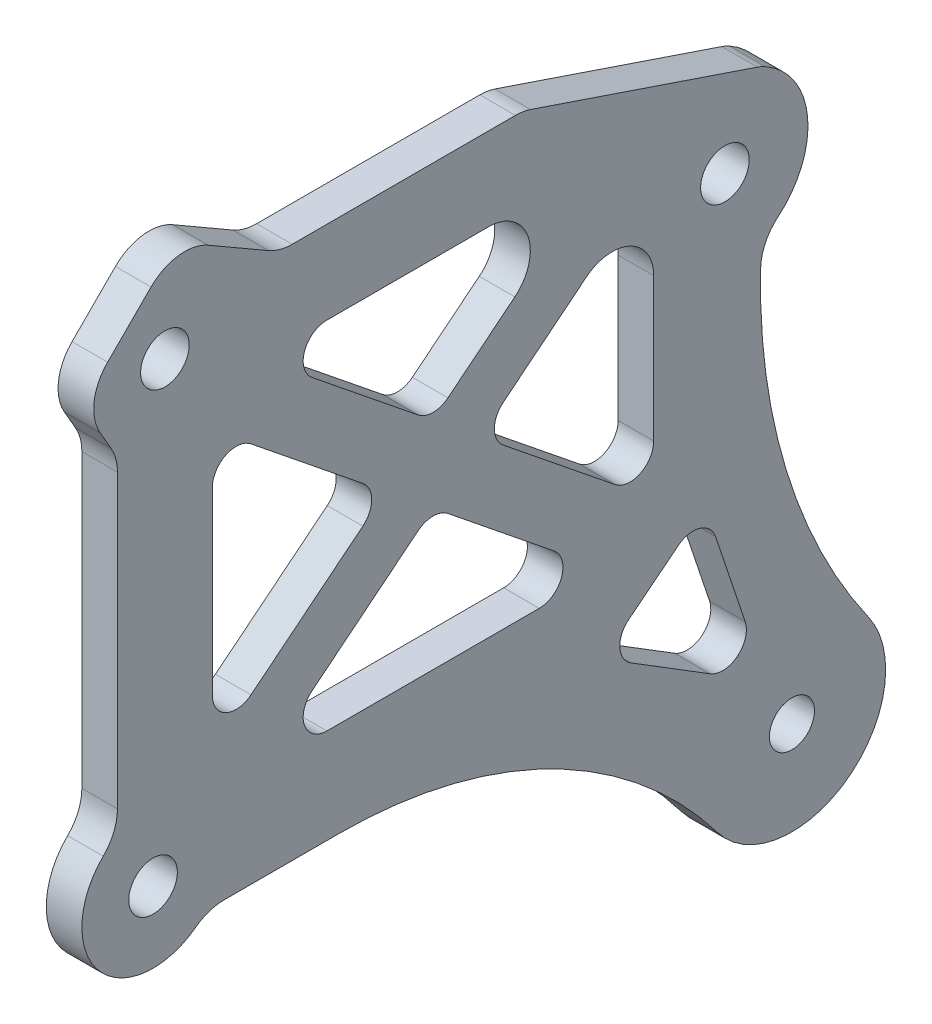
SolidWorks part; units mm, degrees
material "Thornel Mat VMA"
ref_plane "前视基准面" through (0, 0, 0) normal (0, 0, 1) x (1, 0, 0)
ref_plane "上视基准面" through (0, 0, 0) normal (0, 1, 0) x (1, 0, 0)
ref_plane "右视基准面" through (0, 0, 0) normal (1, 0, 0) x (0, 0, -1)
sketch "草图1" plane through (0, 0, 0) normal (1, 0, 0) x (0, 0, -1)
  line L25 (1, 37.9868) -> (63, -4.0132) construction
  line L26 (-3, -4) -> (48.2719, -4) construction
  line L31 (-3, -4) -> (-3, 40.9868) construction
  line L32 (-3, 40.9868) -> (51.2, 40.9868)
  line L34 (1, 37.9868) -> (63, 37.9868) construction
  line L35 (1, 37.9868) -> (1, -4.0132) construction
  line L36 (1, -4.0132) -> (63, -4.0132) construction
  line L37 (63, 37.9868) -> (63, -4.0132) construction
  line L38 (1, 37.9868) -> (53.8469, -15.0717) construction
  line L39 (1, 37.9868) -> (67.6564, 3.8558) construction
  line L41 (48.2719, -9.4744) -> (48.2719, -4) construction
  line L44 (-3, 40.9868) -> (-3, 5.1962)
  line L45 (4.4721, -4) -> (15.6689, -4)
  line L46 (51.2, 34.2246) -> (51.2, 40.9868)
  line L47 (38.2165, 33.9868) -> (23.6, 22.2045)
  line L48 (42.2, 4) -> (5, 4) construction
  line L49 (42.2, 4) -> (42.2, 33.9868) construction
  line L50 (42.2, 33.9868) -> (5, 33.9868) construction
  line L51 (5, 4) -> (5, 33.9868) construction
  line L52 (42.2, 4) -> (5, 33.9868) construction
  line L53 (42.2, 33.9868) -> (5, 4) construction
  line L54 (8.9835, 4) -> (23.6, 15.7823)
  line L55 (8.9835, 33.9868) -> (23.6, 22.2045)
  line L56 (5, 30.7757) -> (19.6165, 18.9934)
  line L57 (8.9835, 33.9868) -> (38.2165, 33.9868)
  line L58 (42.2, 30.7757) -> (42.2, 7.2111)
  line L59 (8.9835, 4) -> (38.2165, 4)
  line L60 (5, 30.7757) -> (5, 7.2111)
  line L61 (19.6165, 18.9934) -> (5, 7.2111)
  line L62 (27.5835, 18.9934) -> (42.2, 7.2111)
  line L63 (27.5835, 18.9934) -> (42.2, 30.7757)
  line L64 (23.6, 15.7823) -> (38.2165, 4)
  circle A0 centre (0, 0) radius 2.05
  circle A1 centre (48.2, 27.9) radius 2.05
  circle A4 centre (1, 37.9868) radius 2.05
  circle A5 centre (63, -4.0132) radius 1.9 construction
  arc A6 (53.8469, -15.0717) -> (67.6564, 3.8558) centre (1, 37.9868) ccw construction
  arc A7 (55.1877, -16.4178) -> (69.3476, 2.9898) centre (1, 37.9868) ccw construction
  arc A8 (52.5061, -13.7255) -> (65.9652, 4.7218) centre (1, 37.9868) ccw construction
  arc A9 (52.5061, -13.7255) -> (55.1877, -16.4178) centre (53.8469, -15.0717) ccw construction
  arc A10 (69.3476, 2.9898) -> (65.9652, 4.7218) centre (67.6564, 3.8558) ccw construction
  arc A11 (53.8469, -15.0717) -> (67.6564, 3.8558) centre (1, 37.9868) ccw construction
  arc A12 (59.4219, -20.669) -> (74.6881, 0.2552) centre (1, 37.9868) ccw construction
  arc A13 (48.2719, -9.4744) -> (60.6246, 7.4564) centre (1, 37.9868) ccw construction
  arc A14 (48.2719, -9.4744) -> (59.4219, -20.669) centre (53.8469, -15.0717) ccw construction
  arc A15 (74.6881, 0.2552) -> (60.6246, 7.4564) centre (67.6564, 3.8558) ccw construction
  circle A19 centre (53.8469, -15.0717) radius 1.9
  arc A20 (-3, 5.1962) -> (4.4721, -4) centre (0, 0) ccw
  arc A21 (47.5503, -19.8427) -> (15.6689, -4) centre (15.6689, -44) ccw
  arc A22 (47.5503, -19.8427) -> (59.4219, -20.669) centre (53.8469, -15.0717) ccw
  arc A23 (51.3147, 21.6311) -> (60.3079, -10.5257) centre (101.2, 18.2464) ccw
  arc A24 (59.4219, -20.669) -> (60.3079, -10.5257) centre (53.8469, -15.0717) ccw
  arc A25 (51.3147, 21.6311) -> (51.2, 34.2246) centre (48.2, 27.9) ccw
  point P8 (23.6, 18.9934)
  point P17 (61.4965, -6.1513)
  point P26 (61.4965, -6.1513)
  dimension "D3" = 4.1
  dimension "D4" = 3
  dimension "D9" = 4
  dimension "D6" = 3
  dimension "D7" = 3
  dimension "D8" = 4.1
  dimension "D10" = 37.9868
  dimension "D13" = 3.8
  dimension "D14" = 11
  dimension "D16" = 6
  dimension "D17" = 12
  dimension "D18" = 40
  dimension "D20" = 14
  dimension "D1" = 27.9
  dimension "D2" = 48.2
  dimension "D5" = 4
  dimension "D11" = 62
  dimension "D12" = 42
  dimension "D15" = 7
  dimension "D19" = 50
  dimension "D21" = 8
  dimension "D22" = 7
  dimension "D23" = 6
  dimension "D24" = 8
  dimension "D25" = 5
  dimension "D26" = 5
extrude "凸台-拉伸1" add sketch "草图1" along normal blind 3
sketch "草图2" plane through (3, 0, 0) normal (1, 0, 0) x (0, 0, -1)
  line L1 (2, 45.9868) -> (-3, 40.9868)
  line L2 (-3.867, 15.4678) -> (-3, -4) construction
  line L3 (-3, 40.9868) -> (-6, 37.9868)
  line L4 (-3, 40.9868) -> (-3, -4) construction
  line L7 (-3, 40.9868) -> (-3, -1.0781) construction
  line L8 (4.4721, -4) -> (15.6689, -4) construction
  line L9 (-6, 37.9868) -> (-3, 32.7907)
  line L11 (2, 45.9868) -> (10.6603, 40.9868)
  line L12 (-3, 40.9868) -> (51.2, 40.9868) construction
  line L13 (-3, 40.9868) -> (10.6603, 40.9868)
  line L14 (-3, 40.9868) -> (-3, 32.7907)
  line M13 (51.2, 40.9868) -> (-3, 40.9868)
  line M32 (-3, 40.9868) -> (-3, 5.1962)
  dimension "D1" = 2.55
  dimension "D2" = 30
  dimension "D3" = 5
  dimension "D4" = 45
  dimension "D5" = 30
  dimension "D6" = 3
extrude "凸台-拉伸2" add sketch "草图2" along direction (1, 0, 0) on the side against the normal up to surface (3 mm away) contours L11 L1 M13 | L3 L9 M32
sketch "草图3" plane through (3, 0, 0) normal (1, 0, 0) x (0, 0, -1)
  line L0 (51.2, 34.2246) -> (31.2, 40.9868)
  line L1 (10.6603, 40.9868) -> (51.2, 40.9868) construction
  line L2 (31.2, 40.9868) -> (51.2, 40.9868)
  line L3 (51.2, 34.2246) -> (51.2, 40.9868) construction
  line L4 (51.2, 40.9868) -> (51.2, 34.2246)
  dimension "D1" = 20
extrude "切除-拉伸1" cut sketch "草图3" against normal blind 10
fillet "圆角1" radius 2 10 edges at (1.5, 22.2045, -23.6) (1.5, 33.9868, -8.9835) (1.5, 18.9934, -19.6165) (1.5, 7.2111, -42.2) (1.5, 18.9934, -27.5835) (1.5, 4, -8.9835) (1.5, 15.7823, -23.6) (1.5, 4, -38.2165) (1.5, 7.2111, -5) (1.5, 30.7757, -5)
fillet "圆角2" radius 4 9 edges at (1.5, 40.9868, -10.6603) (1.5, 45.9868, -2) (1.5, -4, -4.4721) (1.5, 21.6311, -51.3147) (1.5, 34.2246, -51.2) (1.5, 40.9868, -31.2) (1.5, 5.1962, 3) (1.5, 32.7907, 3) (1.5, 37.9868, 6)
fillet "圆角3" radius 3.5 2 edges at (1.5, 30.7757, -42.2) (1.5, 33.9868, -38.2165)
sketch "草图4" plane through (3, 0, 0) normal (1, 0, 0) x (0, 0, -1)
  line L0 (37.8632, -2.3495) -> (46.5124, 4.4978)
  line L1 (46.5124, 4.4978) -> (51.661, -10.8921)
  line L2 (51.661, -10.8921) -> (37.8632, -2.3495)
extrude "切除-拉伸2" cut sketch "草图4" against normal blind 10
fillet "圆角4" radius 2 3 edges at (1.5, -10.8921, -51.661) (1.5, 4.4978, -46.5124) (1.5, -2.3495, -37.8632)
